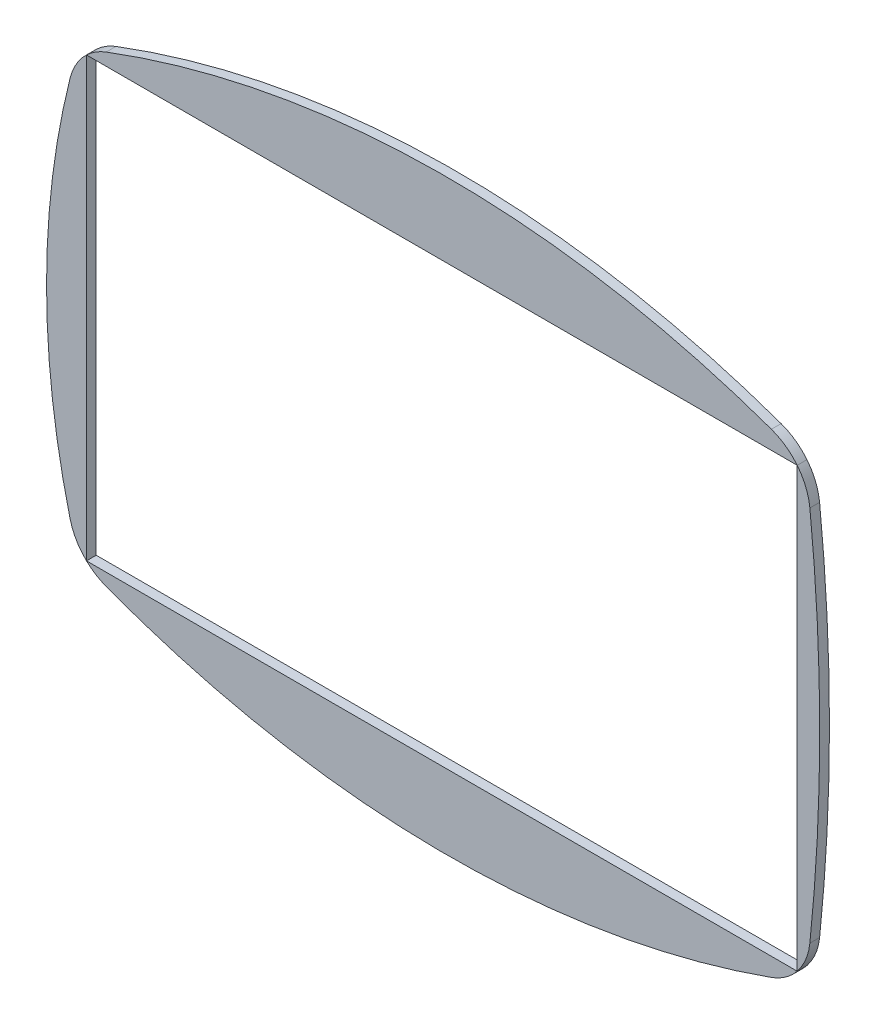
SolidWorks part; units mm, degrees
ref_plane "Front Plane" through (0, 0, 0) normal (0, 0, 1) x (1, 0, 0)
ref_plane "Top Plane" through (0, 0, 0) normal (0, 1, 0) x (1, 0, 0)
ref_plane "Right Plane" through (0, 0, 0) normal (1, 0, 0) x (0, 0, -1)
sketch "Sketch1" plane through (0, 0, 0) normal (0, 0, 1) x (1, 0, 0)
  line L0 (-153, 130) -> (3, 130) construction
  line L1 (-156, 130) -> (-153, 130) construction
  line L2 (-156, -5) -> (-156, 130) construction
  line L3 (-156, -5) -> (-153, -5) construction
  line L4 (-153, -5) -> (3, -5) construction
  line L5 (-153, 130) -> (3, 130)
  line L6 (-156, 130) -> (-153, 130)
  line L7 (-156, -5) -> (-156, 130)
  line L8 (-156, -5) -> (-153, -5)
  line L9 (-153, -5) -> (3, -5)
  line L10 (-156, 62.5) -> (52.0862, 62.5) construction
  line L11 (3, 130) -> (3, 127) construction
  line L12 (-116.6615, -5) -> (-56.6615, -5)
  line L16 (3, -2) -> (3, 127) construction
  line L17 (3, -2) -> (3, -5) construction
  line L18 (3, 130) -> (3, 127)
  line L19 (3, -2) -> (3, 127)
  line L20 (3, -2) -> (3, -5)
  line L22 (-156, -5) -> (-216, -5)
  line L23 (-156, -5) -> (-156, 130)
  line L24 (-156, 130) -> (-216, 130)
  line L25 (-216, -5) -> (-216, 130)
  arc A0 (-4.9552, -10.6456) -> (6.8967, 4.4311) centre (-11.0052, 6.3072) ccw
  arc A1 (-4.9552, -10.6456) -> (-209.9248, -8.8197) centre (-104.9521, 269.5569) cw
  arc A2 (6.8967, 4.4311) -> (6.8967, 120.5689) centre (-547.2104, 62.5) ccw
  arc A3 (-209.9248, -8.8197) -> (-221.0322, 3.6404) centre (-203.5738, 8.0226) cw
  arc A4 (-221.0322, 3.6404) -> (-221.0322, 121.3596) centre (13.4561, 62.5) cw
  arc A5 (-4.9552, 135.6456) -> (6.8967, 120.5689) centre (-11.0052, 118.6928) cw
  arc A6 (-4.9552, 135.6456) -> (-209.9248, 133.8197) centre (-104.9521, -144.5569) ccw
  arc A7 (-209.9248, 133.8197) -> (-221.0322, 121.3596) centre (-203.5738, 116.9774) ccw
  point P9 (9, -11)
  point P22 (-219.3567, -5)
  point P24 (-222, -11)
  point P25 (-204.4305, -16.1612)
  point P26 (0, 0)
  point P27 (9.9311, 62.5)
  point P29 (-220.5033, 1.7794)
  point P38 (-220.8638, 120.6115)
  dimension "D6" = 18
  dimension "D3" = 18
  dimension "D1" = 6
  dimension "D2" = 6
  dimension "D4" = 6
  dimension "D5" = 6
  dimension "D9" = 60
extrude "Boss-Extrude1" add sketch "Sketch1" against normal blind 3 contours L25 A7 A4 A3 | A3 A1 A0 L9 L8 L22 | A6 A7 L24 L6 L5 A5 | L10 L19 L20 A0 A2 | L19 L10 A2 A5 L18
